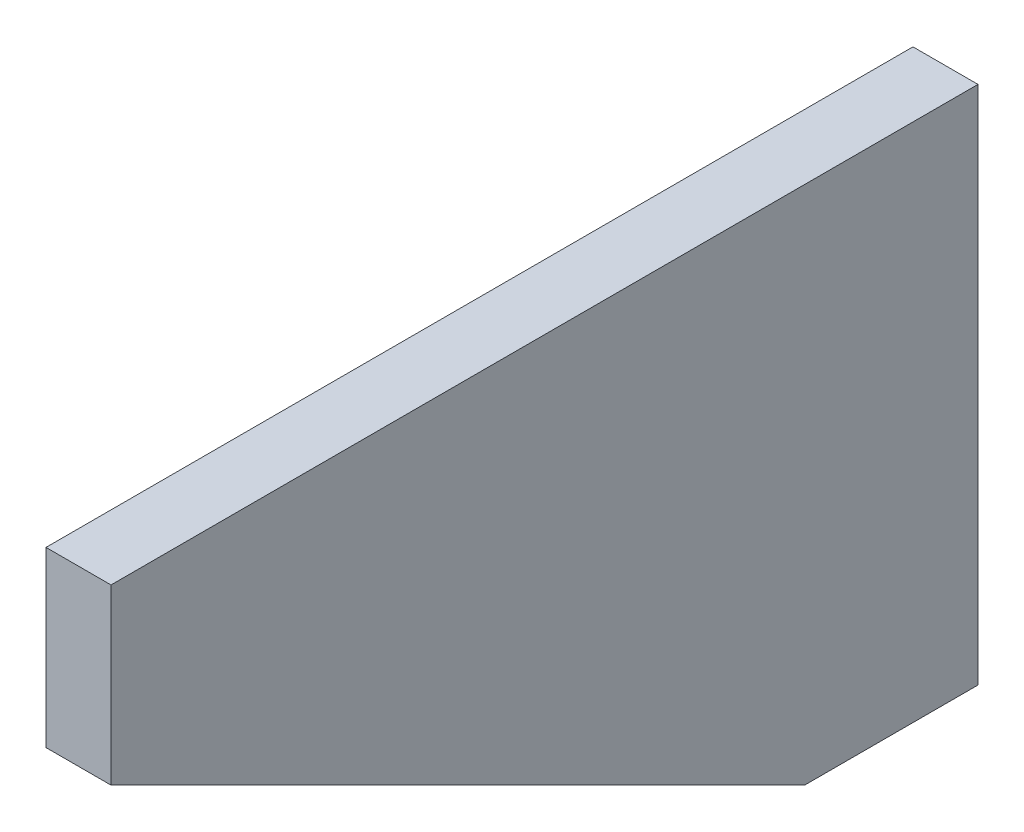
SolidWorks part; units mm, degrees
material "Low Carbon Steel"
ref_plane "Front Plane" through (0, 0, 0) normal (0, 0, 1) x (1, 0, 0)
ref_plane "Top Plane" through (0, 0, 0) normal (0, 1, 0) x (1, 0, 0)
ref_plane "Right Plane" through (0, 0, 0) normal (1, 0, 0) x (0, 0, -1)
sketch "Sketch1" plane through (0, 0, 0) normal (1, 0, 0) x (0, 0, -1)
  line L0 (0, 0) -> (0, -76.2)
  line L1 (0, -76.2) -> (-25.4, -76.2)
  line L2 (-25.4, -76.2) -> (-127, -25.4)
  line L3 (-127, -25.4) -> (-127, 0)
  line L4 (-127, 0) -> (0, 0)
  dimension "D1" = 127
  dimension "D2" = 76.2
  dimension "D3" = 25.4
  dimension "D4" = 25.4
extrude "Boss-Extrude1" add sketch "Sketch1" along normal blind 9.525
